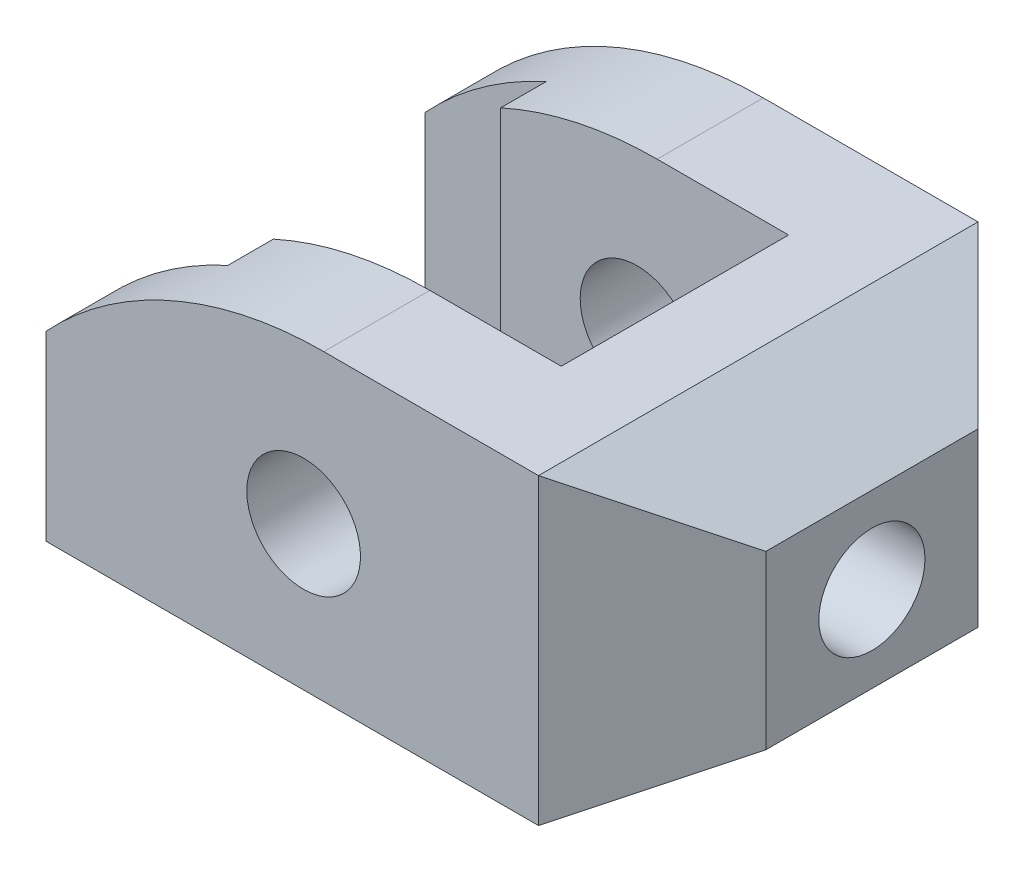
SolidWorks part; units mm, degrees
material "1060 Alloy"
ref_plane "Front Plane" through (0, 0, 0) normal (0, 0, 1) x (1, 0, 0)
ref_plane "Top Plane" through (0, 0, 0) normal (0, 1, 0) x (1, 0, 0)
ref_plane "Right Plane" through (0, 0, 0) normal (1, 0, 0) x (0, 0, -1)
sketch "Sketch1" plane through (0, 0, 0) normal (0, 0, 1) x (1, 0, 0)
  line L0 (0, 0) -> (65, 0)
  line L1 (0, 0) -> (0, 24)
  line L2 (65, 0) -> (80, 8.6603)
  line L3 (80, 8.6603) -> (80, 31.3397)
  line L4 (80, 31.3397) -> (65, 40)
  line L5 (65, 40) -> (36.6606, 40)
  arc A0 (36.6606, 40) -> (0, 24) centre (36.6606, -10) ccw
  circle A1 centre (34, 19) radius 7.5
  dimension "D8" = 50
  dimension "D9" = 31
  dimension "D11" = 15
  dimension "D1" = 65
  dimension "D2" = 24
  dimension "D3" = 15
  dimension "D4" = 15
  dimension "D5" = 40
  dimension "D6" = 30
  dimension "D7" = 30
  dimension "D10" = 19
extrude "Boss-Extrude1" add sketch "Sketch1" along normal mid plane 58
sketch "Sketch2" plane through (0, 0, 0) normal (0, 1, 0) x (1, 0, 0)
  line L0 (0, -29) -> (0, 29) construction
  line L1 (0, 21) -> (16, 21)
  line L2 (0, 21) -> (0, -21)
  line L3 (0, -21) -> (16, -21)
  line L4 (16, 21) -> (16, 15)
  line L5 (36.6606, 29) -> (0, 29) construction
  line L6 (16, 15) -> (54, 15)
  line L8 (16, -15) -> (54, -15)
  line L9 (54, 15) -> (54, -15)
  line L10 (0, -29) -> (36.6606, -29) construction
  line L11 (65, -29) -> (65, 29) construction
  line L12 (16, -15) -> (16, -21)
  dimension "D1" = 8
  dimension "D2" = 8
  dimension "D3" = 6
  dimension "D4" = 6
  dimension "D5" = 11
  dimension "D6" = 16
extrude "Cut-Extrude1" cut sketch "Sketch2" along normal blind 72 and the other way through all
sketch "Sketch3" plane through (0, 0, 0) normal (0, 1, 0) x (1, 0, 0)
  line L0 (80, 29) -> (65, 29)
  line L1 (65, 29) -> (80, 14)
  line L2 (80, -29) -> (80, 29) construction
  line L3 (80, 14) -> (80, 29)
  line L4 (65, -29) -> (80, -14)
  line L5 (80, -14) -> (80, -29)
  line L6 (80, -29) -> (65, -29) construction
  line L7 (80, -29) -> (65, -29)
  dimension "D1" = 45
  dimension "D2" = 45
extrude "Cut-Extrude2" cut sketch "Sketch3" along normal blind 72
sketch "Sketch4" plane through (80, 0, 0) normal (1, 0, 0) x (0, 0, -1)
  line L0 (-29, 0) -> (29, 0) construction
  line L1 (29, 40) -> (29, 0) construction
  circle A0 centre (0, 20) radius 7
  dimension "D1" = 14
  dimension "D2" = 20
  dimension "D3" = 29
extrude "Cut-Extrude3" cut sketch "Sketch4" against normal through all both and the other way through all
equation "\"a\"= 58"
equation "\"b\"= 40"
equation "\"c\"= 65"
